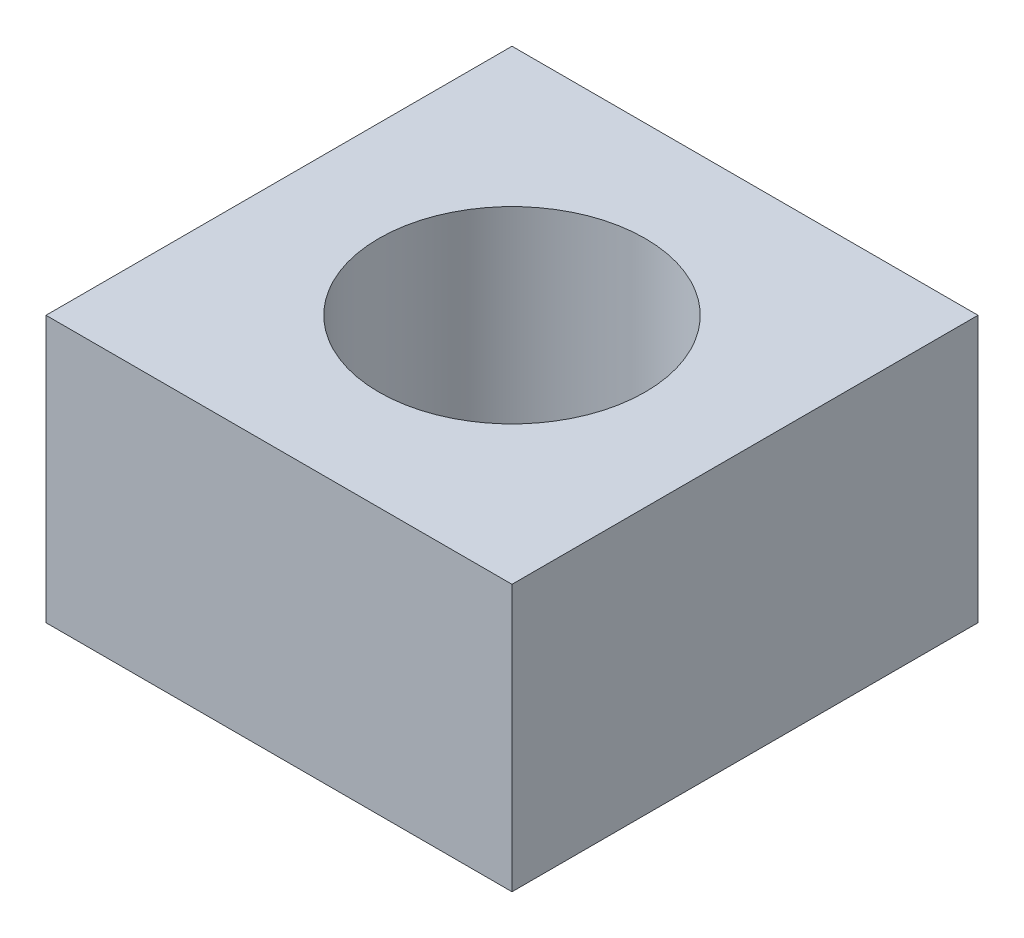
SolidWorks part; units mm, degrees
ref_plane "Front Plane" through (0, 0, 0) normal (0, 0, 1) x (1, 0, 0)
ref_plane "Top Plane" through (0, 0, 0) normal (0, 1, 0) x (1, 0, 0)
ref_plane "Right Plane" through (0, 0, 0) normal (1, 0, 0) x (0, 0, -1)
sketch "Sketch1" plane through (0, 0, 0) normal (0, 1, 0) x (1, 0, 0)
  line L1 (-3.5, -3.5) -> (3.5, -3.5)
  line L2 (-3.5, -3.5) -> (-3.5, 3.5)
  line L3 (-3.5, 3.5) -> (3.5, 3.5)
  line L4 (3.5, -3.5) -> (3.5, 3.5)
  line L5 (-3.5, -3.5) -> (3.5, 3.5) construction
  line L6 (-3.5, 3.5) -> (3.5, -3.5) construction
  circle A0 centre (0, 0) radius 2
  point P0 (0, 0)
  dimension "D2" = 4
  dimension "D1" = 7
extrude "Boss-Extrude1" add sketch "Sketch1" along normal blind 4
